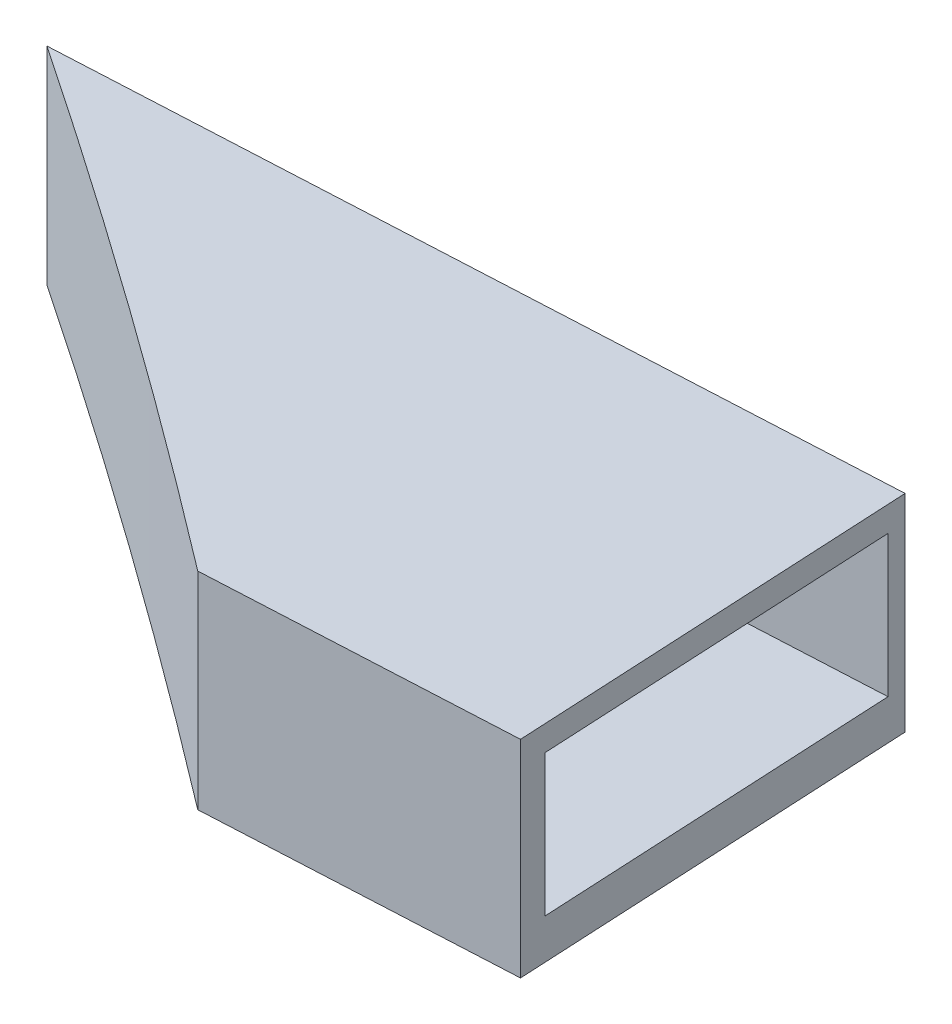
SolidWorks part; units mm, degrees
ref_plane "Front Plane" through (0, 0, 0) normal (0, 0, 1) x (1, 0, 0)
ref_plane "Top Plane" through (0, 0, 0) normal (0, 1, 0) x (1, 0, 0)
ref_plane "Right Plane" through (0, 0, 0) normal (1, 0, 0) x (0, 0, -1)
sketch "Sketch1" plane through (0, 0, 0) normal (0, 1, 0) x (1, 0, 0)
  line L0 (550.3864, 820.8197) -> (625.4403, 824.6477)
  line L5 (625.4403, 824.6477) -> (627.3402, 787.3977)
  line L6 (627.3402, 787.3977) -> (599.116, 785.9582)
  arc A0 (599.116, 785.9582) -> (550.3864, 820.8197) centre (0, 0) ccw
  point P7 (547.8466, 823.4133)
  point P8 (740.8608, 657.3031)
extrude "Boss-Extrude2" add sketch "Sketch1" along normal blind 19
sketch "Sketch3" plane through (665.7678, 0, -33.956) normal (0.9987, 0, -0.0509) x (-0.0509, 0, -0.9987)
  line L1 (756.8108, 16.6894) -> (790.0608, 16.6894)
  line L2 (756.8108, 16.6894) -> (756.8108, 3.6894)
  line L3 (756.8108, 3.6894) -> (790.0608, 3.6894)
  line L4 (790.0608, 16.6894) -> (790.0608, 3.6894)
extrude "Cut-Extrude2" cut sketch "Sketch3" against normal blind 19
